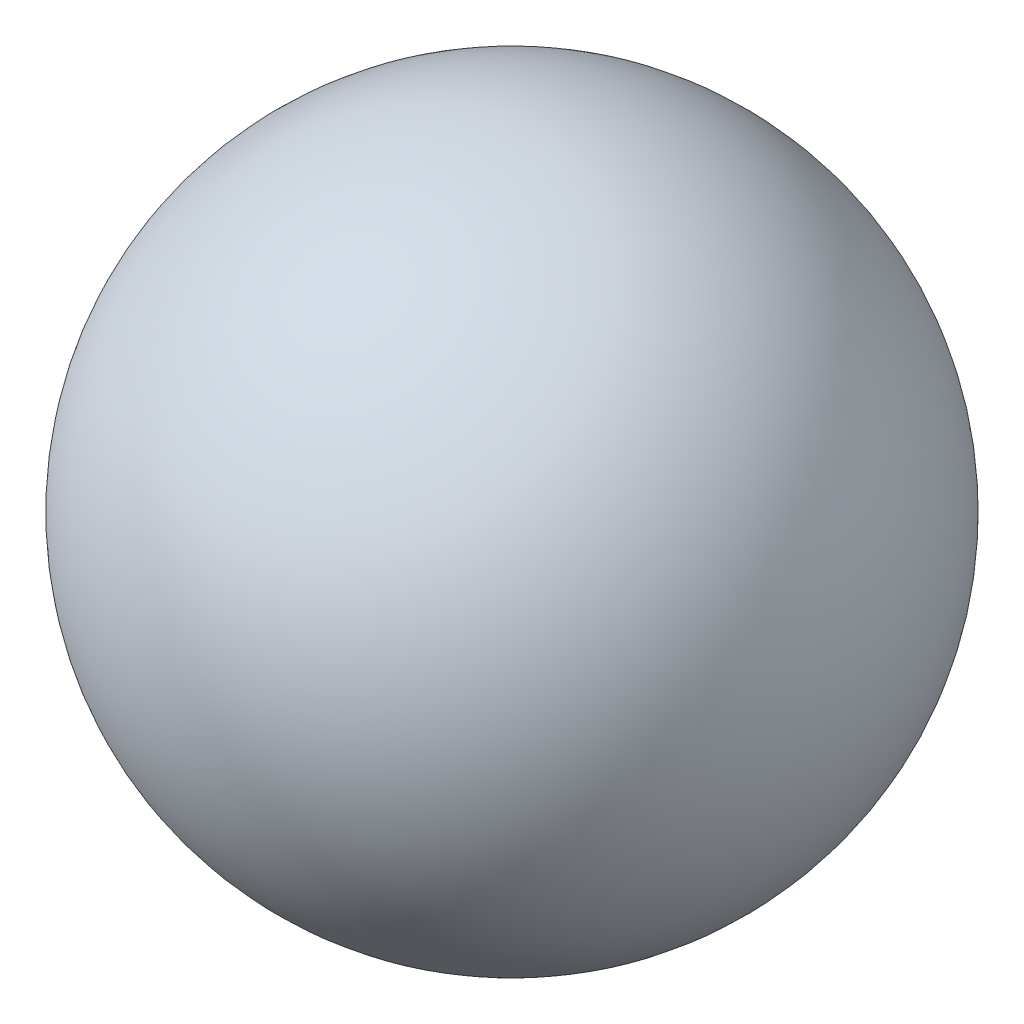
SolidWorks part; units mm, degrees
ref_plane "Front Plane" through (0, 0, 0) normal (0, 0, 1) x (1, 0, 0)
ref_plane "Top Plane" through (0, 0, 0) normal (0, 1, 0) x (1, 0, 0)
ref_plane "Right Plane" through (0, 0, 0) normal (1, 0, 0) x (0, 0, -1)
sketch "Sketch1" plane through (0, 0, 0) normal (0, 0, 1) x (1, 0, 0)
  line L0 (0, 47.3449) -> (0, 53.9768) construction
  line L1 (0, 2.78) -> (0, -2.78)
  arc A0 (0, 2.78) -> (0, -2.78) centre (0, 0) cw
  dimension "D1" = 2.78
revolve "Revolve1" add sketch "Sketch1" angle 360 about L0
